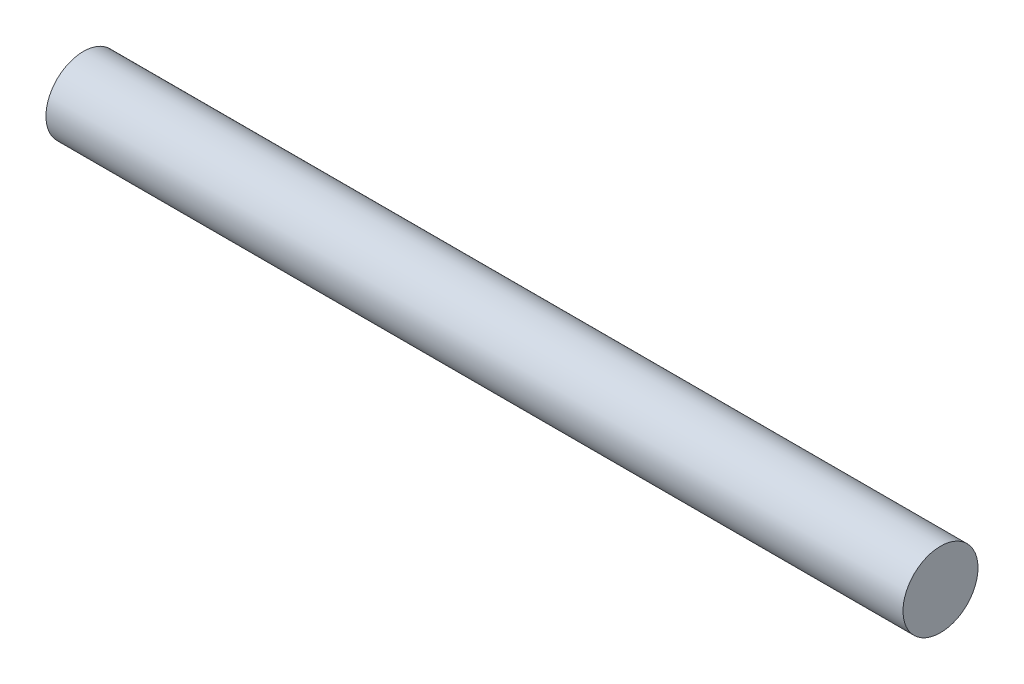
SolidWorks part; units mm, degrees
ref_plane "Front Plane" through (0, 0, 0) normal (0, 0, 1) x (1, 0, 0)
ref_plane "Top Plane" through (0, 0, 0) normal (0, 1, 0) x (1, 0, 0)
ref_plane "Right Plane" through (0, 0, 0) normal (1, 0, 0) x (0, 0, -1)
sketch "Sketch1" plane through (0, 0, 0) normal (1, 0, 0) x (0, 0, -1)
  circle A0 centre (0, 0) radius 3.5
  dimension "D1" = 7
extrude "Boss-Extrude1" add sketch "Sketch1" along normal blind 80 contours A0
